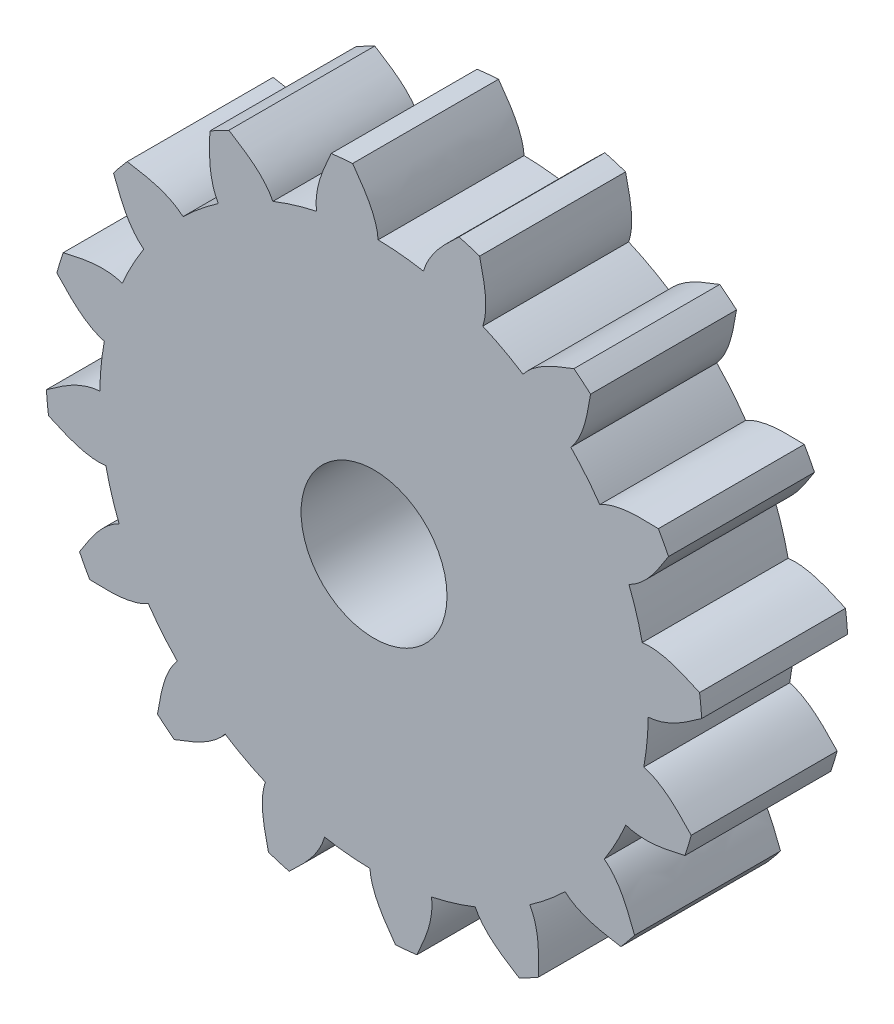
SolidWorks part; units mm, degrees
ref_plane "Front Plane" through (0, 0, 0) normal (0, 0, 1) x (1, 0, 0)
ref_plane "Top Plane" through (0, 0, 0) normal (0, 1, 0) x (1, 0, 0)
ref_plane "Right Plane" through (0, 0, 0) normal (1, 0, 0) x (0, 0, -1)
sketch "punti involuta" plane through (0, 0, 0) normal (0, 0, 1) x (1, 0, 0)
  line L0 (0, 0) -> (0, 4.6277) construction
  line L1 (-3.4916, 2) -> (3.4916, 2) construction
  line L2 (-3.4916, 0.7292) -> (3.4916, 3.2708) construction
  line L3 (0, 0) -> (-0.6428, 1.766) construction
  line L4 (-0.6428, 1.766) -> (0, 2) construction
  line L5 (-1.2414, 1.411) -> (-0.2023, 2.3252) construction
  line L6 (-0.3539, 1.8458) -> (0.0233, 1.9181) construction
  circle A0 centre (0, 0) radius 2 construction
  circle A1 centre (0, 0) radius 1.8794 construction
  arc A2 (-0.6428, 1.766) -> (-1.2414, 1.411) centre (0, 0) ccw construction
  arc A3 (-0.6428, 1.766) -> (-0.3539, 1.8458) centre (0, 0) cw construction
  arc A4 (-0.6428, 1.766) -> (0.028, 1.8792) centre (0, 0) cw construction
  point P4 (0, 2)
  point P7 (0, 2)
  dimension "D1" = 4
  dimension "D2" = 20
  dimension "D3" = 0.684
  dimension "D5" = 1.384
  dimension "D7" = 0.384
  dimension "D4" = 0.7
  dimension "D6" = 0.3
  dimension "D8" = 0.684
sketch "diametro testa" plane through (0, 0, 0) normal (0, 0, 1) x (1, 0, 0)
  circle A0 centre (0, 0) radius 2.25
  dimension "D1" = 4.5
sketch "profilo" plane through (0, 0, 0) normal (0, 0, 1) x (1, 0, 0)
  line L0 (0, 0) -> (-0.1842, 1.8703) construction
  line L1 (0, 0) -> (0, 4.6277) construction
  line L2 (-0.1842, 1.8703) -> (-0.2205, 2.2392)
  arc A1 (-0.2205, 2.2392) -> (-0.1467, 2.2452) centre (0, 0) cw
  circle A3 centre (0, 0) radius 2.25 construction
  arc A4 (0.028, 1.8792) -> (-0.1842, 1.8703) centre (0, 0) ccw
  arc A5 (0.028, 1.8792) -> (-0.6428, 1.766) centre (0, 0) ccw construction
  circle A6 centre (0, 0) radius 1.8794 construction
  spline S0 degree 3 poles (-0.2023, 2.3252) (-0.1183, 2.1969) (0.0168, 2.0487) (0.028, 1.8792) knots 0 0 0 0 1 1 1 1
  dimension "D1" = 5.625
sketch "diametro base" plane through (0, 0, 0) normal (0, 0, 1) x (1, 0, 0)
  circle A0 centre (0, 0) radius 1.8794
extrude "Boss-Extrude7" add sketch "profilo" along normal blind 1 contours S0 A1 L2 A4
ref_plane "Plane1" through (0, 0, 0) normal (0.9952, 0.098, 0) x (-0.098, 0.9952, 0)
mirror "Mirror1" about plane through (0, 0, 0) normal (0.9952, 0.098, 0) of bodies 112
pattern_circular "CirPattern1" count 16 over 360 about axis through (0, 0, 1) along (0, 0, 1) of bodies 113
extrude "Boss-Extrude9" add sketch "diametro base" along normal up to surface (1 mm away)
sketch "mozzo" plane through (0, 0, 0) normal (0, 0, 1) x (1, 0, 0)
  circle A0 centre (0, 0) radius 0.5
  dimension "D1" = 1
extrude "Cut-Extrude1" cut sketch "mozzo" along normal up to surface (1 mm away) up to face at (0, 0, 1)
equation "\"n_imposto\"= 16"
equation "\"m\"= .25"
equation "\"d_imposto\"= \"n_imposto\" * \"m\""
equation "\"alpha\"= 20"
equation "\"a1\"= .7"
equation "\"a2\"= .3"
equation "\"s\"= 1"
equation "\"D1@punti involuta\"=\"d_imposto\""
equation "\"D2@punti involuta\" = \"alpha\""
equation "\"D4@punti involuta\" = \"a1\""
equation "\"D5@punti involuta\" = \"D3@punti involuta\" + \"a1\""
equation "\"D6@punti involuta\" = \"a2\""
equation "\"D7@punti involuta\" = \"D3@punti involuta\" - \"a2\""
equation "\"D1@diametro testa\"=\"d_imposto\" + \"m\" * 2"
equation "\"D8@punti involuta\"=\"D3@punti involuta\""
equation "\"D1@profilo\"=360 / \"n_imposto\" / 4"
equation "\"D1@Boss-Extrude7\"=\"s\""
equation "\"D1@CirPattern1\"= \"n_imposto\""
equation "\"d_mozzo\"= 1"
equation "\"D1@mozzo\"=\"d_mozzo\""
